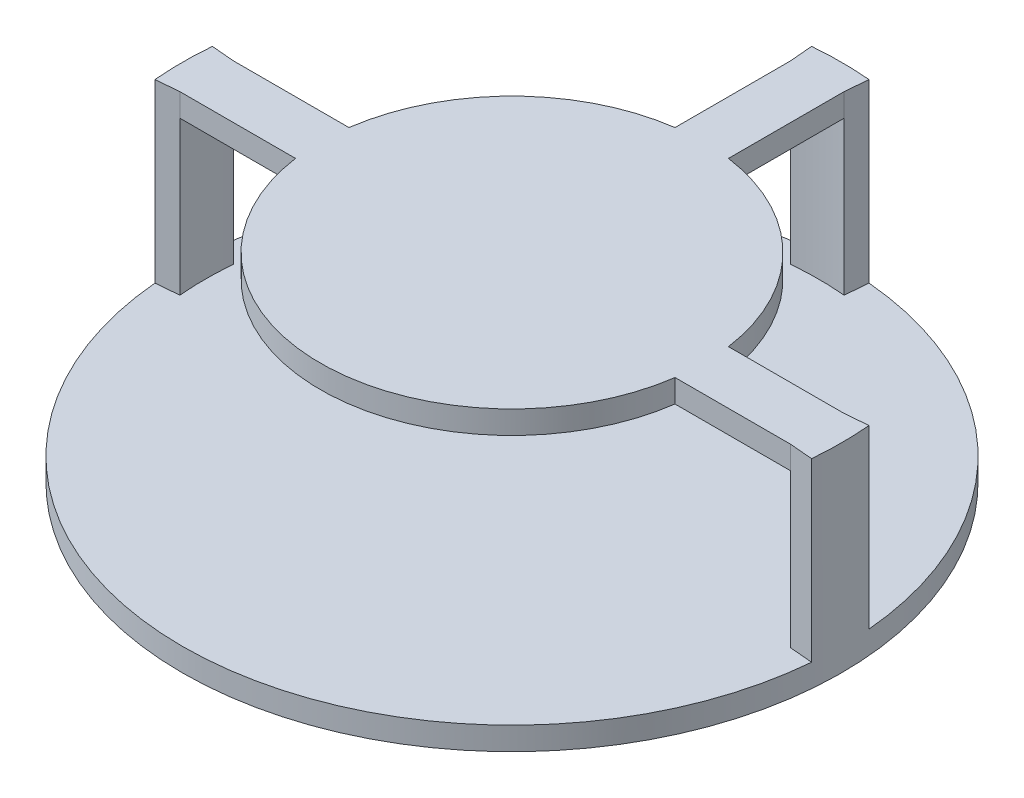
SolidWorks part; units mm, degrees
ref_plane "Front Plane" through (0, 0, 0) normal (0, 0, 1) x (1, 0, 0)
ref_plane "Top Plane" through (0, 0, 0) normal (0, 1, 0) x (1, 0, 0)
ref_plane "Right Plane" through (0, 0, 0) normal (1, 0, 0) x (0, 0, -1)
ref_plane "Plane1" through (0, 0, 0) normal (0, 1, 0) x (1, 0, 0)
sketch "Sketch1" plane through (0, 0, 0) normal (0, 1, 0) x (1, 0, 0)
  circle A0 centre (0, 0) radius 43
extrude "Boss-Extrude1" add sketch "Sketch1" along normal blind 3
sketch "Sketch2" plane through (0, 3, 0) normal (0, 1, 0) x (1, 0, 0)
  line L0 (0, 0) -> (-43, 0)
  line L1 (0, 0) -> (43, 0)
  line L2 (0, 0) -> (0, 43)
  line L3 (0, 0) -> (-42.8364, 3.7477)
  line L4 (0, 0) -> (-42.8364, -3.7477)
  line L5 (0, 0) -> (-3.7477, 42.8364)
  line L6 (0, 0) -> (3.7477, 42.8364)
  line L7 (0, 0) -> (42.8364, 3.7477)
  line L8 (0, 0) -> (42.8364, -3.7477)
  circle A0 centre (0, 0) radius 40
  circle A1 centre (0, 0) radius 43 construction
  circle A2 centre (0, 0) radius 43
  circle M8 centre (0, 0) radius 43
extrude "Boss-Extrude2" add sketch "Sketch2" along normal blind 20 contours A0 L3 L0 M8 | A0 L0 L4 M8 | A0 L1 L7 M8 | A0 L8 L1 M8 | A0 L6 L2 M8 | A0 L2 L5 M8
ref_plane "Plane2" through (0, 23, 0) normal (0, 1, 0) x (1, 0, 0)
sketch "Sketch3" plane through (0, 23, 0) normal (0, 1, 0) x (1, 0, 0)
  line L0 (0, 0) -> (-42.8364, 3.7477)
  line L1 (0, 0) -> (-42.8364, -3.7477)
  line L2 (0, 0) -> (-3.7477, 42.8364)
  line L3 (0, 0) -> (3.7477, 42.8364)
  line L4 (0, 0) -> (42.8364, 3.7477)
  line L5 (39.8477, 3.4862) -> (42.8364, 3.7477) construction
  line L6 (0, 0) -> (42.8364, -3.7477)
  line L7 (39.8477, -3.4862) -> (17.8005, -3.4862)
  line L8 (39.8477, 3.4862) -> (18.9191, 3.4862)
  line L9 (3.4862, 39.8477) -> (3.4862, 19.6959)
  line L10 (3.4862, 19.6959) -> (4.7979, 16.2006)
  line L11 (4.7979, 16.2006) -> (5.0775, 16.2006)
  line L12 (-3.4862, 39.8477) -> (-3.4862, 19.6959)
  line L13 (-39.8477, 3.4862) -> (-16.4537, 3.4862)
  line L14 (-39.8477, -3.4862) -> (-16.4537, -3.4862)
  circle A0 centre (0, 0) radius 25
  circle A1 centre (0, 0) radius 43
extrude "Boss-Extrude3" add sketch "Sketch3" along normal blind 3
